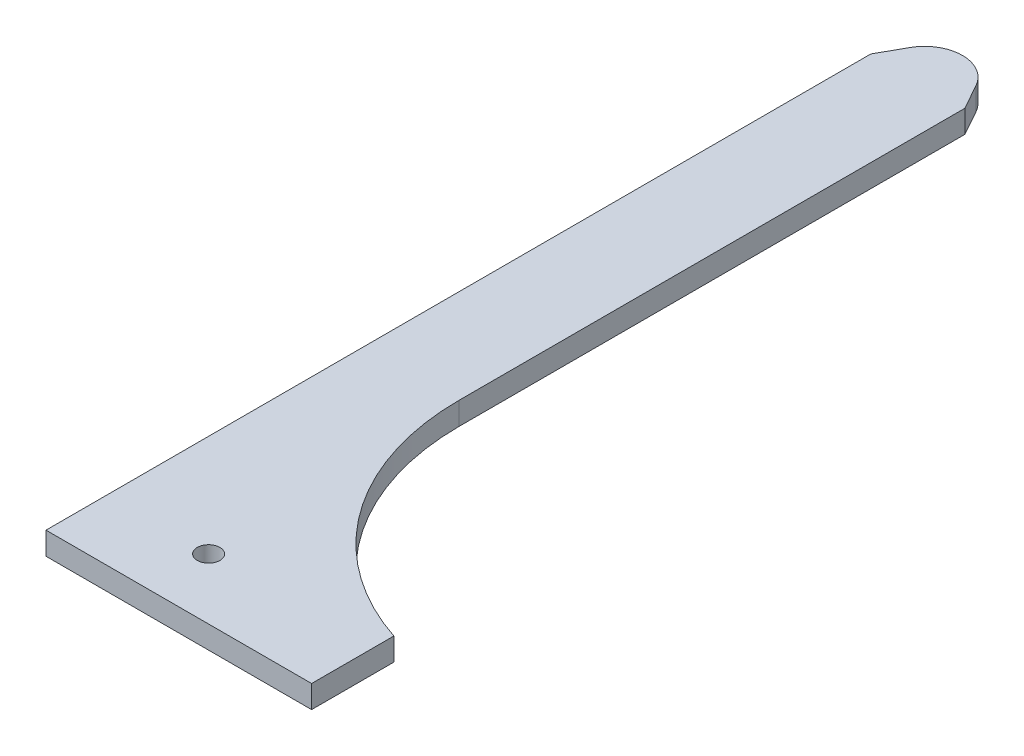
SolidWorks part; units mm, degrees
ref_plane "前视基准面" through (0, 0, 0) normal (0, 0, 1) x (1, 0, 0)
ref_plane "上视基准面" through (0, 0, 0) normal (0, 1, 0) x (1, 0, 0)
ref_plane "右视基准面" through (0, 0, 0) normal (1, 0, 0) x (0, 0, -1)
other "Configuration Table"
sketch "草图1" plane through (0, 0, 0) normal (0, 1, 0) x (1, 0, 0)
  line L0 (0, 48) -> (0, -48)
  line L1 (0, -48) -> (0, -107.8621)
  line L6 (-45.46, -107.8621) -> (25.79, -107.8621)
  line L11 (-45.46, -107.8621) -> (-45.46, -32.8621)
  line L12 (25.79, -107.8621) -> (25.79, -32.8621)
  line L13 (-45.46, -32.8621) -> (25.79, -32.8621)
  line L14 (25.79, -42.2621) -> (-45.46, -42.2621)
  line L15 (-45.46, -32.8621) -> (5.01, -32.8621)
  line L16 (-45.46, -32.8621) -> (-45.46, 27.8779)
  line L17 (-45.46, 27.8779) -> (5.01, 27.8779)
  line L18 (5.01, -32.8621) -> (5.01, 27.8779)
  line L19 (-10.2743, -42.2621) -> (-10.2743, -31.3598)
  line L20 (-31.96, -42.2621) -> (-31.96, -34.2221) construction
  line L21 (-31.96, -34.2221) -> (-45.46, -34.2221) construction
  line L22 (0, 0) -> (-48, 0) construction
  line L23 (-39.23, 67) -> (-39.23, 78.1855) construction
  line L24 (-33, 0) -> (-45.46, 0)
  line L25 (-33, 0) -> (-33, 67)
  line L26 (-33, 67) -> (-45.46, 67)
  line L27 (-45.46, 0) -> (-45.46, 67)
  line L28 (-39.23, 78.1855) -> (-45.46, 67)
  line L29 (-39.23, 78.1855) -> (-33, 67)
  circle A0 centre (0, 0) radius 33
  circle A1 centre (0, 0) radius 48
  circle A2 centre (-31.96, -34.2221) radius 1.5
  dimension "D1" = 66
  dimension "D2" = 96
  dimension "D11" = 3
  dimension "D3" = 71.25
  dimension "D4" = 25.79
  dimension "D5" = 75
  dimension "D6" = 60.74
  dimension "D7" = 50.47
  dimension "D8" = 9.4
  dimension "D9" = 13.5
  dimension "D10" = 8.04
  dimension "D12" = 67
  dimension "D14" = 12.46
extrude "凸台-拉伸1" add sketch "草图1" along normal blind 3 contours A1 L25 L26 L27 L17 | L25 A1 L17 | A2 L15 L19 A0 L17 L25 L24 L16 A1 | L17 A1 L16 L24 L25 | A1 L17 L27 | A2 A1 L14 L19 L15 | A2 A1 L13 L11 L14 | A1 L16 L13 | A2 L15 A1 | L29 L28 L26
fillet "圆角4" radius 5 1 edges at (-39.23, 1.5, -78.1855)
